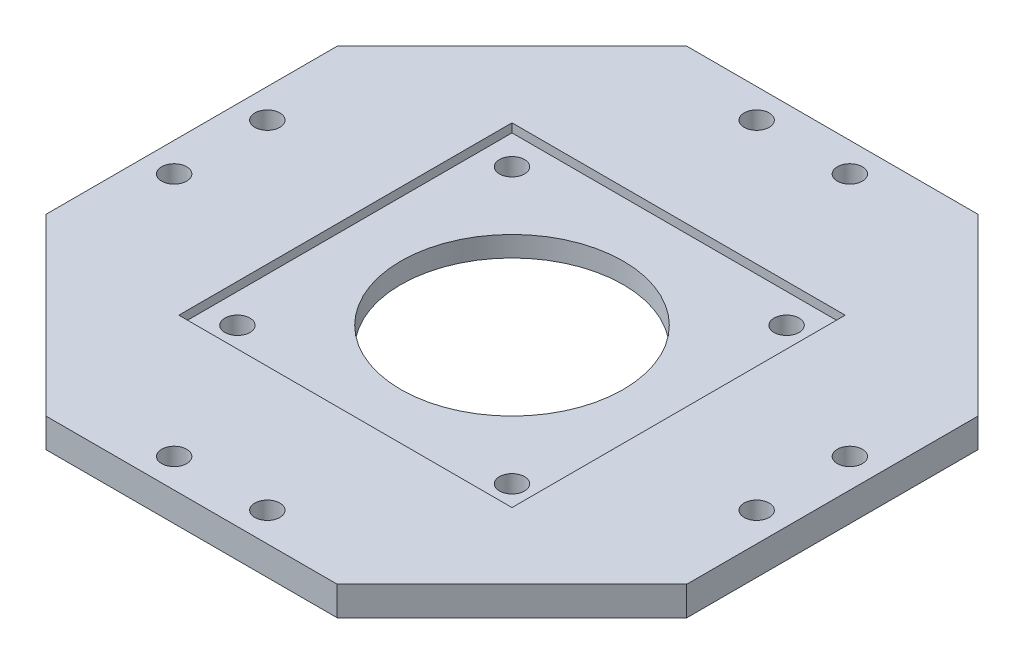
SolidWorks part; units mm, degrees
ref_plane "Front Plane" through (0, 0, 0) normal (0, 0, 1) x (1, 0, 0)
ref_plane "Top Plane" through (0, 0, 0) normal (0, 1, 0) x (1, 0, 0)
ref_plane "Right Plane" through (0, 0, 0) normal (1, 0, 0) x (0, 0, -1)
sketch "Sketch1" plane through (0, 0, 0) normal (0, 1, 0) x (1, 0, 0)
  line L0 (-37, 37) -> (37, -37) construction
  line L1 (30, 0) -> (0, 0) construction
  line L2 (-25, -55) -> (25, -55)
  line L3 (-55, -25) -> (-55, 25)
  line L4 (-25, 55) -> (25, 55)
  line L5 (55, -25) -> (55, 25)
  line L6 (-55, -55) -> (55, 55) construction
  line L7 (-55, 55) -> (55, -55) construction
  line L8 (-23.57, -23.57) -> (23.57, -23.57) construction
  line L9 (-23.57, -23.57) -> (-23.57, 23.57) construction
  line L10 (-23.57, 23.57) -> (23.57, 23.57) construction
  line L11 (23.57, -23.57) -> (23.57, 23.57) construction
  line L12 (-23.57, -23.57) -> (23.57, 23.57) construction
  line L13 (-23.57, 23.57) -> (23.57, -23.57) construction
  line L14 (0, 55) -> (0, 50) construction
  line L15 (0, 50) -> (-8, 50) construction
  line L16 (-55, 25) -> (-25, 55)
  line L17 (25, 55) -> (55, 25)
  line L18 (-25, -55) -> (-55, -25)
  line L19 (25, -55) -> (55, -25)
  circle A0 centre (23.57, 23.57) radius 2.15
  circle A1 centre (-23.57, 23.57) radius 2.15
  circle A2 centre (-23.57, -23.57) radius 2.15
  circle A3 centre (23.57, -23.57) radius 2.15
  circle A4 centre (0, 0) radius 19.1
  circle A5 centre (-8, 50) radius 2.15
  circle A6 centre (8, 50) radius 2.15
  circle A7 centre (50, 8) radius 2.15
  circle A8 centre (50, -8) radius 2.15
  circle A9 centre (8, -50) radius 2.15
  circle A10 centre (-8, -50) radius 2.15
  circle A11 centre (-50, -8) radius 2.15
  circle A12 centre (-50, 8) radius 2.15
  point P2 (0, 0)
  point P39 (0, 0)
  dimension "D1" = 47.14
  dimension "D2" = 110
  dimension "D3" = 110
extrude "Boss-Extrude1" add sketch "Sketch1" along normal blind 5
sketch "Sketch2" plane through (0, 5, 0) normal (0, 1, 0) x (1, 0, 0)
  line L1 (-28.6, -28.6) -> (28.6, -28.6)
  line L2 (-28.6, -28.6) -> (-28.6, 28.6)
  line L3 (-28.6, 28.6) -> (28.6, 28.6)
  line L4 (28.6, -28.6) -> (28.6, 28.6)
  line L5 (-28.6, -28.6) -> (28.6, 28.6) construction
  line L6 (-28.6, 28.6) -> (28.6, -28.6) construction
  point P0 (0, 0)
  dimension "D1" = 57.2
  dimension "57.2" = 57.2
extrude "Cut-Extrude1" cut sketch "Sketch2" against normal blind 1.5
